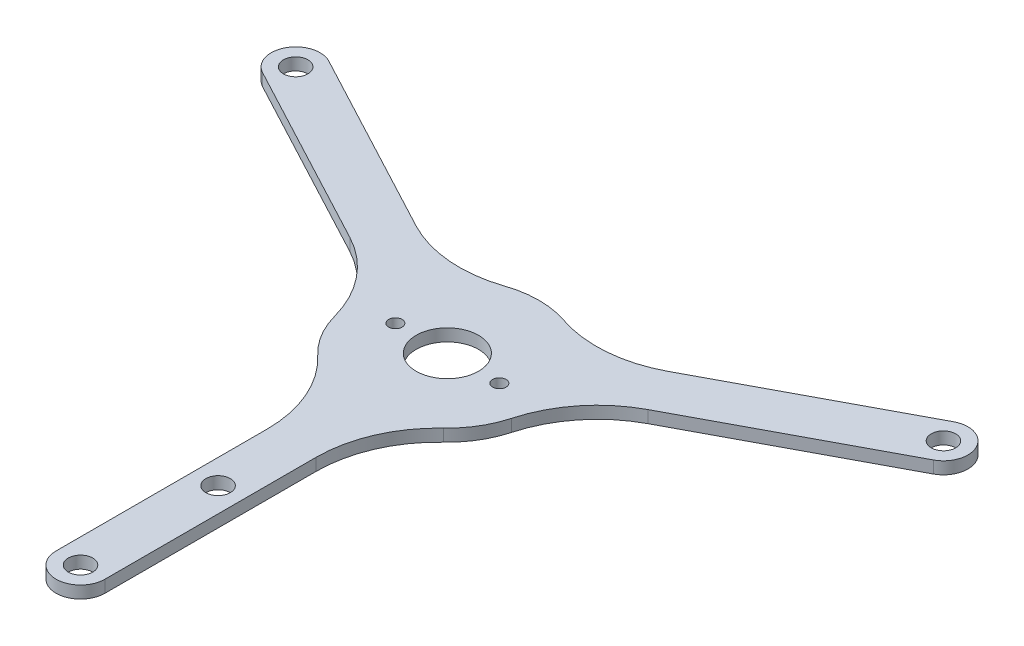
SolidWorks part; units mm, degrees
material "5052-H34"
ref_plane "正面" through (0, 0, 0) normal (0, 0, 1) x (1, 0, 0)
ref_plane "平面" through (0, 0, 0) normal (0, 1, 0) x (1, 0, 0)
ref_plane "右側面" through (0, 0, 0) normal (1, 0, 0) x (0, 0, -1)
sketch "ｽｹｯﾁ1" plane through (0, 0, 0) normal (0, 1, 0) x (1, 0, 0)
  line L0 (0, 5.1) -> (0, 0) construction
  line L1 (0, 0) -> (8.5, 0) construction
  line L2 (-81.3432, 38.7207) -> (-14.6425, 3.2553)
  line L3 (-77.5874, 45.7842) -> (-10.8867, 10.3189)
  line L4 (0, 0) -> (4, -14.4568) construction
  line L5 (0, 0) -> (-14.6425, 3.2553) construction
  line L6 (-4, -60) -> (-4, -59.8665)
  line L7 (4, -60) -> (4, -59.8665)
  line L8 (77.5874, 45.7842) -> (10.8867, 10.3189)
  line L9 (81.3432, 38.7207) -> (14.6425, 3.2553)
  line L10 (0, -60) -> (0, -17.5) construction
  line L11 (4, -59.8665) -> (4, -37.5)
  line L12 (4, -37.5) -> (4, -14.4568)
  line L13 (-4, -59.8665) -> (-4, -37.5)
  line L14 (-4, -37.5) -> (-4, -14.4568)
  circle A0 centre (0, 0) radius 5.1
  circle A1 centre (0, 0) radius 60 construction
  circle A4 centre (0, -60) radius 2
  arc A8 (-3.9978, -59.8667) -> (3.9978, -59.8667) centre (0, -60) ccw
  circle A11 centre (8.5, 0) radius 1.1
  circle A12 centre (-8.5, 0) radius 1.1
  circle A13 centre (-52.9769, 28.1683) radius 2
  arc A14 (-50.9823, 31.6355) -> (-54.736, 24.5759) centre (-52.9769, 28.1683) ccw
  arc A15 (50.9823, 31.6355) -> (54.736, 24.5759) centre (52.9769, 28.1683) cw
  arc A16 (4, -14.4568) -> (-4, -14.4568) centre (0, 0) ccw
  circle A17 centre (52.9769, 28.1683) radius 2
  circle A18 centre (8.5, 0) radius 1.1
  arc A19 (-4, -14.4568) -> (4, -14.4568) centre (0, 0) ccw construction
  arc A21 (3.9978, -59.8667) -> (-3.9978, -59.8667) centre (0, -60) ccw construction
  arc A23 (0, -41.5) -> (4, -37.5) centre (0, -37.5) ccw construction
  circle A24 centre (0, -37.5) radius 2
  arc A25 (0, -33.5) -> (-4, -37.5) centre (0, -37.5) ccw construction
  arc A26 (4, -37.5) -> (0, -33.5) centre (0, -37.5) ccw construction
  arc A27 (-4, -37.5) -> (0, -41.5) centre (0, -37.5) ccw construction
  point P15 (0, 0)
  point P23 (0, 0)
  point P45 (0, 0)
  dimension "D1" = 10.2
  dimension "D2" = 120
  dimension "D3" = 4
  dimension "D5" = 2
  dimension "D7" = 15
  dimension "D8" = 2.2
  dimension "D4" = 8
  dimension "D13" = 4
  dimension "D14" = 20
  dimension "D9" = 17
  dimension "D6" = 118
  dimension "D10" = 15
  dimension "D12" = 37.5
extrude "ﾎﾞｽ - 押し出し1" add sketch "ｽｹｯﾁ1" along normal blind 2
fillet "ﾌｨﾚｯﾄ1" radius 20 6 edges at (-10.8867, 1, -10.3189) (10.8867, 1, -10.3189) (14.6425, 1, -3.2553) (4, 1, 14.4568) (-4, 1, 14.4568) (-14.6425, 1, -3.2553)
